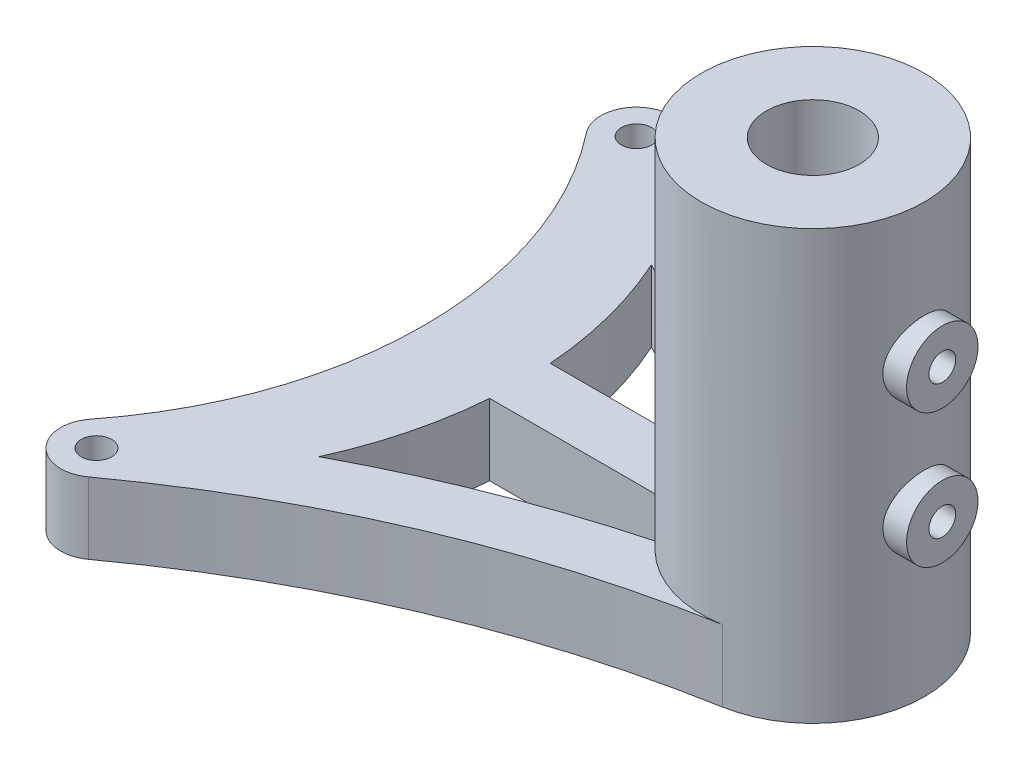
SolidWorks part; units mm, degrees
material "Custom Plastic"
ref_plane "Front Plane" through (0, 0, 0) normal (0, 0, 1) x (1, 0, 0)
ref_plane "Top Plane" through (0, 0, 0) normal (0, 1, 0) x (1, 0, 0)
ref_plane "Right Plane" through (0, 0, 0) normal (1, 0, 0) x (0, 0, -1)
sketch "Sketch1" plane through (0, 0, 0) normal (0, 1, 0) x (1, 0, 0)
  line L0 (0, 0) -> (29.8839, 0) construction
  line L1 (0.515, -3.4) -> (21.2905, -3.4)
  line L2 (0, -3.4) -> (29.8839, -3.4) construction
  line L3 (0.515, 3.4) -> (21.2905, 3.4)
  circle A0 centre (-16.6808, 30.25) radius 1.7
  circle A1 centre (-16.6808, -30.25) radius 1.7
  arc A2 (-14.3262, 33.4835) -> (-19.8276, 27.7806) centre (-16.6808, 30.25) ccw
  arc A3 (-19.8276, -27.7806) -> (-14.3262, -33.4835) centre (-16.6808, -30.25) ccw
  circle A4 centre (33.3192, 0) radius 5.2
  arc A6 (23.6815, 7.9602) -> (21.2905, 3.4) centre (33.3192, 0) ccw
  arc A8 (-19.8276, -27.7806) -> (-19.8276, 27.7806) centre (-55.2287, 0) ccw
  arc A9 (-3.3918, -18.6252) -> (0.515, -3.4) centre (-44.3564, 0) ccw
  arc A10 (35.4884, -12.3104) -> (-14.3262, -33.4835) centre (56.3123, -130.4897) ccw
  arc A11 (35.4884, 12.3104) -> (-14.3262, 33.4835) centre (56.3123, 130.4897) cw
  arc A12 (23.6815, -7.9602) -> (-3.3918, -18.6252) centre (56.3123, -130.4897) ccw
  arc A13 (23.6815, 7.9602) -> (-3.3918, 18.6252) centre (56.3123, 130.4897) cw
  arc A14 (34.3083, 5.6135) -> (-18.329, 27.9865) centre (56.3123, 130.4897) cw construction
  arc A15 (35.4884, -12.3104) -> (35.4884, 12.3104) centre (33.3192, 0) ccw
  arc A16 (-3.3918, 18.6252) -> (0.515, 3.4) centre (-44.3564, 0) cw
  arc A17 (21.2905, -3.4) -> (23.6815, -7.9602) centre (33.3192, 0) ccw
  dimension "D2" = 3.4
  dimension "D3" = 3.4
  dimension "D5" = 8
  dimension "D6" = 8
  dimension "D7" = 10.4
  dimension "D8" = 25
  dimension "D9" = 240
  dimension "D10" = 90
  dimension "D11" = 90
  dimension "D1" = 60.5
  dimension "D4" = 50
  dimension "D12" = 3.4
  dimension "D13" = 6.8
extrude "Boss-Extrude1" add sketch "Sketch1" along normal blind 8
sketch "Sketch2" plane through (0, 8, 0) normal (0, 1, 0) x (1, 0, 0)
  circle A0 centre (33.3192, 0) radius 5.2
  circle A1 centre (33.3192, 0) radius 12.5
  dimension "D1" = 10.4
  dimension "D2" = 25
extrude "Boss-Extrude2" add sketch "Sketch2" along normal blind 40
ref_plane "Plane1" through (45.8192, 0, 0) normal (1, 0, 0) x (0, 0, -1)
sketch "Sketch3" plane through (45.8192, 0, 0) normal (1, 0, 0) x (0, 0, -1)
  line L0 (12.5, 48) -> (-12.5, 48) construction
  circle A0 centre (0, 33) radius 1.5
  circle A1 centre (0, 33) radius 4
  circle A2 centre (0, 18) radius 4
  circle A3 centre (0, 18) radius 1.5
  dimension "D1" = 3
  dimension "D2" = 8
  dimension "D3" = 15
  dimension "D4" = 15
extrude "Boss-Extrude3" add sketch "Sketch3" against normal up to surface (0.0903 mm away)
sketch "Sketch4" plane through (45.8192, 0, 0) normal (1, 0, 0) x (0, 0, -1)
  circle A0 centre (0, 33) radius 1.5
  circle A1 centre (0, 33) radius 4
  circle A2 centre (0, 18) radius 4
  circle A3 centre (0, 18) radius 1.5
  dimension "D1" = 8
  dimension "D2" = 3
  dimension "D3" = 15
extrude "Boss-Extrude4" add sketch "Sketch4" along normal blind 2
sketch "Sketch8" plane through (45.8192, 0, 0) normal (1, 0, 0) x (0, 0, -1)
  circle A0 centre (0, 33) radius 1.5
  circle A1 centre (0, 18) radius 1.5
extrude "Cut-Extrude4" cut sketch "Sketch8" against normal up to surface (7.521 mm away) contours A0 | A1
